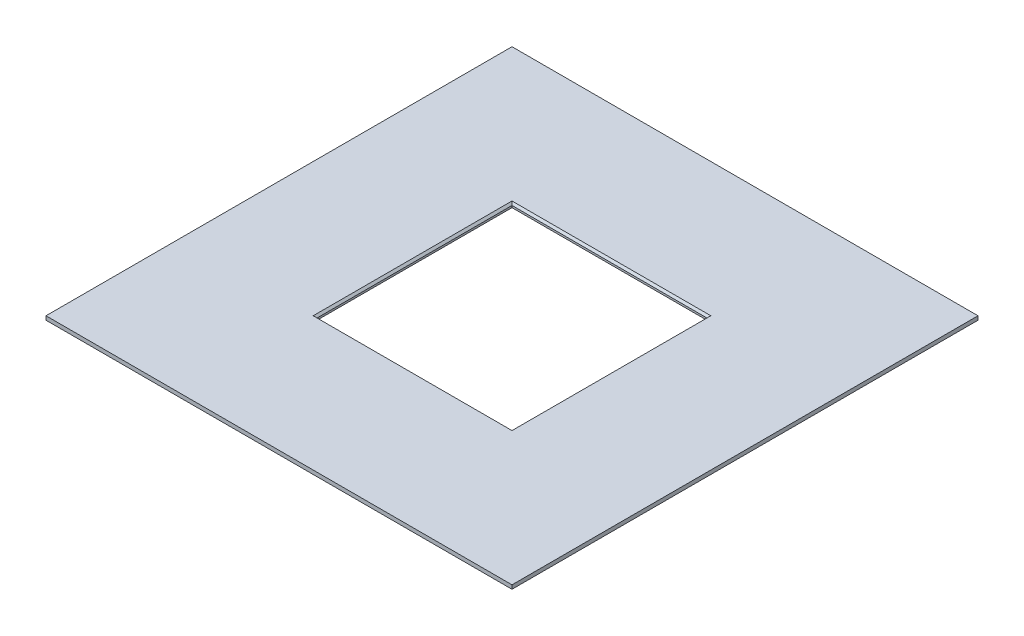
SolidWorks part; units mm, degrees
ref_plane "Front Plane" through (0, 0, 0) normal (0, 0, 1) x (1, 0, 0)
ref_plane "Top Plane" through (0, 0, 0) normal (0, 1, 0) x (1, 0, 0)
ref_plane "Right Plane" through (0, 0, 0) normal (1, 0, 0) x (0, 0, -1)
sketch "Sketch1" plane through (0, 0, 0) normal (0, 1, 0) x (1, 0, 0)
  line L1 (-25.1, 25.1) -> (25.1, 25.1)
  line L2 (-25.1, 25.1) -> (-25.1, -25.1)
  line L3 (-25.1, -25.1) -> (25.1, -25.1)
  line L4 (25.1, 25.1) -> (25.1, -25.1)
  line L5 (-25.1, 25.1) -> (25.1, -25.1) construction
  line L6 (-25.1, -25.1) -> (25.1, 25.1) construction
  line L7 (-60, 60) -> (60, 60)
  line L8 (-60, 60) -> (-60, -60)
  line L9 (-60, -60) -> (60, -60)
  line L10 (60, 60) -> (60, -60)
  line L11 (-60, 60) -> (60, -60) construction
  line L12 (-60, -60) -> (60, 60) construction
  point P0 (0, 0)
  point P6 (0, 0)
  dimension "D1" = 50.2
  dimension "D2" = 50.2
  dimension "D3" = 120
  dimension "D4" = 120
extrude "Boss-Extrude1" add sketch "Sketch1" along normal blind 1
chamfer "Chamfer1" distance 0.5 angle 45 4 edges at (0, 1, 25.1) (25.1, 1, 0) (0, 1, -25.1) (-25.1, 1, 0)
